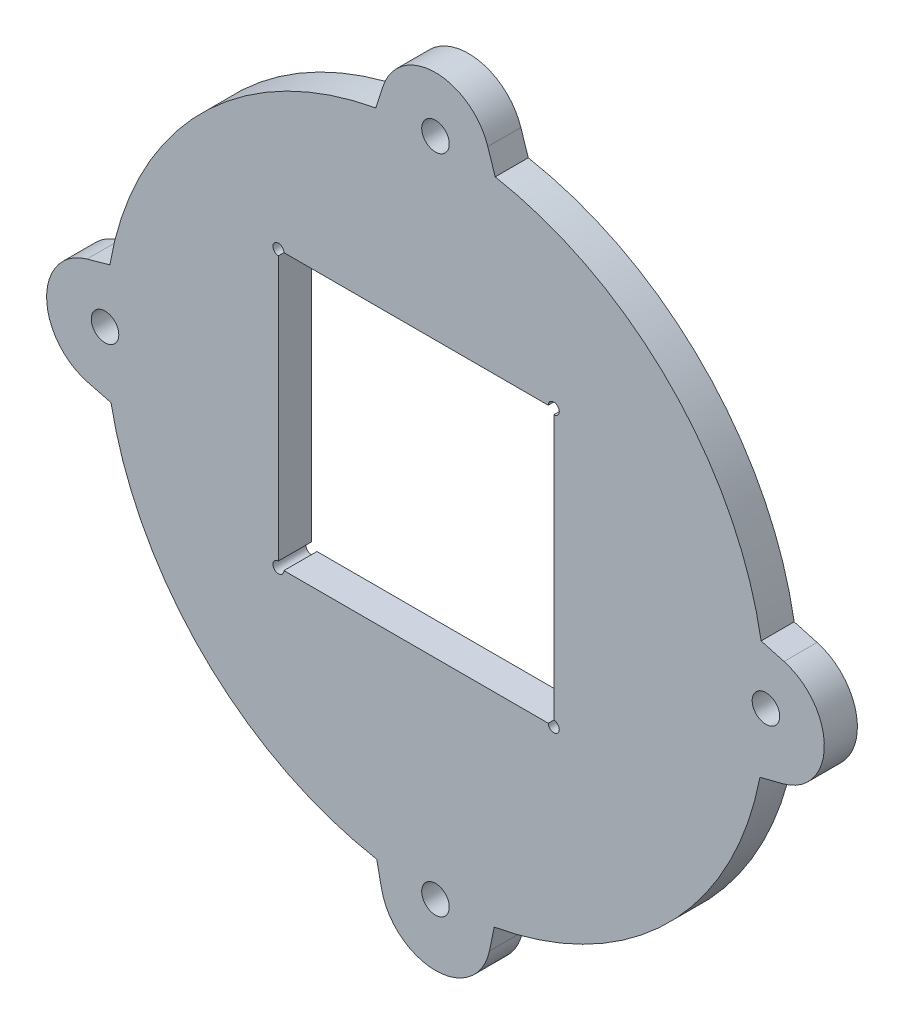
SolidWorks part; units mm, degrees
material "ABS PC"
ref_plane "Front Plane" through (0, 0, 0) normal (0, 0, 1) x (1, 0, 0)
ref_plane "Top Plane" through (0, 0, 0) normal (0, 1, 0) x (1, 0, 0)
ref_plane "Right Plane" through (0, 0, 0) normal (1, 0, 0) x (0, 0, -1)
sketch "Sketch1" plane through (0, 0, 0) normal (0, 0, 1) x (1, 0, 0)
  line L0 (-1.851, -4.0685) -> (-1.851, 25.9315) construction
  line L1 (-33.4933, 0.4465) -> (-31.4155, 1.0246)
  line L2 (-16.1131, -15.1084) -> (8.8869, -15.1084)
  line L3 (-16.1131, -15.1084) -> (-16.1131, 9.8916)
  line L4 (-16.1131, 9.8916) -> (8.8869, 9.8916)
  line L5 (8.8869, -15.1084) -> (8.8869, 9.8916)
  line L6 (-16.1131, -15.1084) -> (8.8869, 9.8916) construction
  line L7 (-16.1131, 9.8916) -> (8.8869, -15.1084) construction
  line L8 (-33.397, -9.2133) -> (-31.3081, -9.7499)
  line L9 (-6.7442, -35.7006) -> (-7.1876, -33.59)
  line L10 (3.0421, -35.7006) -> (3.4856, -33.59)
  line L11 (29.695, -9.2133) -> (27.6061, -9.7499)
  line L12 (29.7913, 0.4465) -> (27.7135, 1.0246)
  line L13 (-6.6029, 27.487) -> (-7.2738, 25.4373)
  line L14 (2.9009, 27.487) -> (3.5718, 25.4373)
  circle A0 centre (-1.851, 25.9315) radius 1.25
  circle A1 centre (28.149, -4.0685) radius 1.25
  circle A2 centre (-1.851, -34.0685) radius 1.25
  circle A3 centre (-31.851, -4.0685) radius 1.25
  circle A4 centre (-1.851, 25.9315) radius 5 construction
  circle A5 centre (-1.851, -4.0685) radius 30 construction
  circle A6 centre (28.451, -4.3705) radius 5 construction
  circle A7 centre (-1.851, -34.6725) radius 5 construction
  circle A8 centre (-32.153, -4.3705) radius 5 construction
  arc A9 (-6.6029, 27.487) -> (2.9009, 27.487) centre (-1.851, 25.9315) cw
  arc A10 (29.7913, 0.4465) -> (29.695, -9.2133) centre (28.451, -4.3705) cw
  arc A11 (3.0421, -35.7006) -> (-6.7442, -35.7006) centre (-1.851, -34.6725) cw
  arc A12 (-33.397, -9.2133) -> (-33.4933, 0.4465) centre (-32.153, -4.3705) cw
  arc A13 (-31.4155, 1.0246) -> (-7.2738, 25.4373) centre (-1.851, -4.0685) cw
  arc A14 (3.5718, 25.4373) -> (27.7135, 1.0246) centre (-1.851, -4.0685) cw
  arc A15 (27.6061, -9.7499) -> (3.4856, -33.59) centre (-1.851, -4.0685) cw
  arc A16 (-7.1876, -33.59) -> (-31.3081, -9.7499) centre (-1.851, -4.0685) cw
  point P25 (-1.851, -4.3705)
  dimension "D5" = 10
  dimension "D6" = 60
  dimension "D7" = 2.5
  dimension "D2" = 30
  dimension "D3" = 25
  dimension "D4" = 4
  dimension "D1" = 4
extrude "Boss-Extrude1" add sketch "Sketch1" along normal blind 3
sketch "Sketch2" plane through (0, 0, 3) normal (0, 0, 1) x (1, 0, 0)
  circle A0 centre (-16.1131, 9.8916) radius 0.5
  circle A1 centre (8.8869, 9.8916) radius 0.5
  circle A2 centre (8.8869, -15.1084) radius 0.5
  circle A3 centre (-16.1131, -15.1084) radius 0.5
  dimension "D1" = 1
extrude "Cut-Extrude1" cut sketch "Sketch2" against normal blind 10
